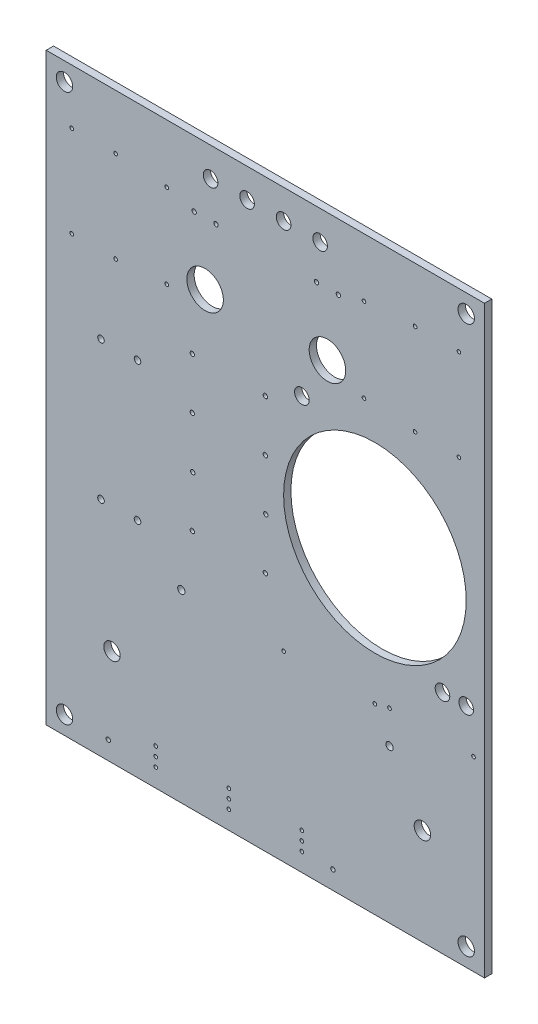
SolidWorks part; units mm, degrees
ref_plane "Спереди" through (0, 0, 0) normal (0, 0, 1) x (1, 0, 0)
ref_plane "Сверху" through (0, 0, 0) normal (0, 1, 0) x (1, 0, 0)
ref_plane "Справа" through (0, 0, 0) normal (1, 0, 0) x (0, 0, -1)
sketch "Эскиз1" plane through (0, 0, 0) normal (0, 0, 1) x (1, 0, 0)
  line L0 (-63.4221, 0) -> (70.5642, 0) construction
  line L1 (0, 51.5662) -> (0, -47.8522) construction
  line L2 (-51, 0) -> (-28, 0) construction
  line L3 (-60, -80) -> (60, -80)
  line L4 (-60, -80) -> (-60, 80)
  line L5 (-60, 80) -> (60, 80)
  line L6 (60, -80) -> (60, 80)
  circle A0 centre (-55, -75) radius 2.25
  circle A1 centre (55, -75) radius 2.25
  circle A2 centre (55, 75) radius 2.25
  circle A3 centre (-55, 75) radius 2.25
  circle A4 centre (30, 7) radius 25
  dimension "D3" = 4.5
  dimension "D6" = 50
  dimension "D1" = 120
  dimension "D2" = 160
  dimension "D4" = 5
  dimension "D5" = 5
  dimension "D7" = 90
  dimension "D8" = 87
  dimension "D11" = 80
extrude "Вытянуть1" add sketch "Эскиз1" along normal blind 2
sketch "Эскиз2" plane through (0, 0, 2) normal (0, 0, 1) x (1, 0, 0)
  line L0 (-60, -80) -> (60, -80) construction
  line L1 (-60, 80) -> (-60, -80) construction
  line L2 (-43, -75) -> (36.4081, -75) construction
  line L3 (-30, -64.6595) -> (-30, -83.93) construction
  line L4 (-10, -64.5241) -> (-10, -83.7946) construction
  line L5 (10, -64.5241) -> (10, -83.7946) construction
  line L6 (-29.4108, 72) -> (29.4956, 72) construction
  line L7 (55, -18) -> (48.4963, -18) construction
  line L8 (-60, 80) -> (-60, -80) construction
  line L9 (-60, 80) -> (-60, -80) construction
  circle A0 centre (-42, -53.5) radius 2.25
  circle A1 centre (43, -53.5) radius 2.25
  circle A2 centre (-43, -75) radius 0.6
  circle A3 centre (18.5, -75) radius 0.6
  circle A4 centre (-30, -70) radius 0.5
  circle A5 centre (-30, -72.5) radius 0.5
  circle A6 centre (-30, -75) radius 0.5
  circle A7 centre (-10, -70) radius 0.5
  circle A8 centre (-10, -72.5) radius 0.5
  circle A9 centre (-10, -75) radius 0.5
  circle A10 centre (10, -70) radius 0.5
  circle A11 centre (10, -72.5) radius 0.5
  circle A12 centre (10, -75) radius 0.5
  circle A13 centre (-15, 72) radius 2
  circle A14 centre (-5, 72) radius 2
  circle A15 centre (5, 72) radius 2
  circle A16 centre (15, 72) radius 2
  circle A17 centre (10, 33) radius 2
  circle A18 centre (55, -18) radius 2
  circle A19 centre (48.5, -18) radius 2
  dimension "D4" = 103
  dimension "D5" = 4.5
  dimension "D6" = 1.2
  dimension "D10" = 1
  dimension "D11" = 5
  dimension "D12" = 5
  dimension "D13" = 7.5
  dimension "D15" = 2.5
  dimension "D17" = 2.5
  dimension "D18" = 2.5
  dimension "D19" = 4
  dimension "D21" = 10
  dimension "D22" = 10
  dimension "D23" = 20
  dimension "D27" = 4
  dimension "D1" = 26.5
  dimension "D2" = 26.5
  dimension "D3" = 18
  dimension "D7" = 5
  dimension "D8" = 17
  dimension "D9" = 78.5
  dimension "D14" = 20
  dimension "D16" = 20
  dimension "D20" = 152
  dimension "D24" = 45
  dimension "D25" = 70
  dimension "D26" = 113
  dimension "D28" = 62
  dimension "D29" = 108.5
  dimension "D30" = 115
  dimension "D31" = 30
extrude "Вырез-Вытянуть1" cut sketch "Эскиз2" against normal blind 2
sketch "Эскиз3" plane through (0, 0, 2) normal (0, 0, 1) x (1, 0, 0)
  line L0 (-16.5, 45) -> (17, 45) construction
  line L1 (-60, -80) -> (60, -80) construction
  line L2 (-60, 80) -> (-60, -80) construction
  line L3 (-30.9219, 62) -> (30.7658, 62) construction
  circle A0 centre (-16.5, 45) radius 5
  circle A1 centre (17, 45) radius 5
  circle A2 centre (-19.5, 62) radius 0.6
  circle A3 centre (-13.5, 62) radius 0.6
  circle A4 centre (14, 62) radius 0.6
  circle A5 centre (20, 62) radius 0.6
  circle A6 centre (34, -38) radius 1
  circle A7 centre (-23, -29.5) radius 1
  dimension "D1" = 10
  dimension "D6" = 6
  dimension "D7" = 6
  dimension "D10" = 1.2
  dimension "D15" = 2
  dimension "D5" = 17
  dimension "D8" = 3
  dimension "D2" = 125
  dimension "D3" = 43.5
  dimension "D4" = 77
  dimension "D9" = 74
  dimension "D11" = 50.5
  dimension "D12" = 37
  dimension "D13" = 94
  dimension "D14" = 42
extrude "Вырез-Вытянуть2" cut sketch "Эскиз3" against normal blind 2
sketch "Эскиз4" plane through (0, 0, 2) normal (0, 0, 1) x (1, 0, 0)
  line L0 (-60, -80) -> (60, -80) construction
  line L1 (-45, 19) -> (-35, 19) construction
  line L2 (-45, -19) -> (-35, -19) construction
  line L3 (-60, 80) -> (-60, -80) construction
  line L4 (-22.8407, -28) -> (10.3042, -28) construction
  line L5 (-22.7145, -14) -> (10.4304, -14) construction
  line L6 (-22.7145, 0) -> (10.4304, 0) construction
  line L7 (-22.8407, 14) -> (10.3042, 14) construction
  line L8 (-22.7145, 28) -> (10.4304, 28) construction
  circle A0 centre (-45, 19) radius 0.9
  circle A1 centre (-35, 19) radius 0.9
  circle A2 centre (-35, -19) radius 0.9
  circle A3 centre (-45, -19) radius 0.9
  circle A6 centre (-20, -14) radius 0.6
  circle A7 centre (0, -14) radius 0.6
  circle A8 centre (-19.8738, 0) radius 0.6
  circle A9 centre (0.1262, 0) radius 0.6
  circle A10 centre (-20, 14) radius 0.6
  circle A11 centre (0, 14) radius 0.6
  circle A12 centre (-20, 28) radius 0.6
  circle A13 centre (0, 28) radius 0.6
  dimension "D3" = 10
  dimension "D4" = 61
  dimension "D7" = 1.8
  dimension "D9" = 66
  dimension "D17" = 20
  dimension "D18" = 20
  dimension "D19" = 20
  dimension "D20" = 20
  dimension "D5" = 99
  dimension "D6" = 15
  dimension "D8" = 15
  dimension "D10" = 40
  dimension "D12" = 14
  dimension "D13" = 14
  dimension "D14" = 14
  dimension "D15" = 14
extrude "Вырез-Вытянуть3" cut sketch "Эскиз4" against normal blind 2
sketch "Эскиз5" plane through (0, 0, 2) normal (0, 0, 1) x (1, 0, 0)
  line L0 (-53, 40) -> (-53, 66.8053) construction
  line L1 (-60, 80) -> (-60, -80) construction
  line L3 (-53, 40) -> (-37.7421, 40) construction
  line L4 (-41, 40) -> (-41, 66.7059) construction
  line L6 (41, 40) -> (41, 66.8053) construction
  line L7 (41, 40) -> (56.2579, 40) construction
  line L8 (53, 40) -> (53, 66.2925) construction
  line L9 (53, 40) -> (68.2579, 40) construction
  line L10 (-27, 41) -> (-27, 64) construction
  circle A0 centre (-53, 40) radius 0.5
  circle A1 centre (-53, 65) radius 0.5
  circle A2 centre (-41, 40) radius 0.5
  circle A3 centre (-41, 65) radius 0.5
  circle A4 centre (41, 40) radius 0.5
  circle A5 centre (41, 65) radius 0.5
  circle A6 centre (53, 40) radius 0.5
  circle A7 centre (53, 65) radius 0.5
  circle A8 centre (-27, 41) radius 0.5
  circle A9 centre (-27, 64) radius 0.5
  circle A10 centre (27, 41) radius 0.5
  circle A11 centre (27, 64) radius 0.5
  circle A12 centre (34, -29) radius 0.5
  circle A13 centre (57, -29) radius 0.5
  circle A14 centre (5, -30) radius 0.5
  circle A15 centre (30, -30) radius 0.5
  dimension "D3" = 25
  dimension "D4" = 1
  dimension "D7" = 7
  dimension "D8" = 25
  dimension "D9" = 25
  dimension "D10" = 25
  dimension "D11" = 87
  dimension "D15" = 23
  dimension "D16" = 23
  dimension "D21" = 1
  dimension "D22" = 23
  dimension "D29" = 25
  dimension "D5" = 12
  dimension "D6" = 12
extrude "Вырез-Вытянуть4" cut sketch "Эскиз5" against normal blind 2
